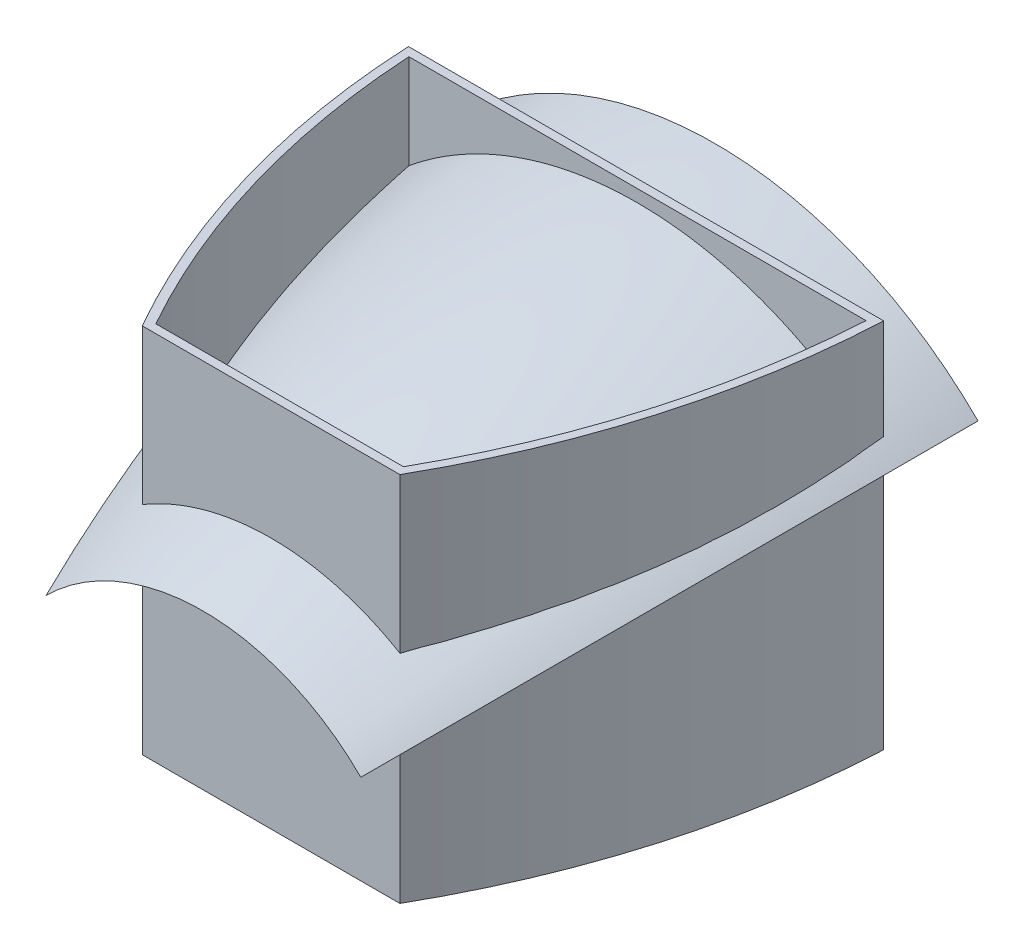
SolidWorks part; units mm, degrees
ref_plane "Спереди" through (0, 0, 0) normal (0, 0, 1) x (1, 0, 0)
ref_plane "Сверху" through (0, 0, 0) normal (0, 1, 0) x (1, 0, 0)
ref_plane "Справа" through (0, 0, 0) normal (1, 0, 0) x (0, 0, -1)
sketch "Эскиз1" plane through (0, 0, 0) normal (0, 1, 0) x (1, 0, 0)
  line L1 (0, 0) -> (0, -131) construction
  line L7 (-45, -131) -> (45, -131)
  line L8 (-83, 0) -> (83, 0)
  arc A0 (-45, -131) -> (-83, 0) centre (208.6832, 13.5989) cw
  arc A2 (45, -131) -> (83, 0) centre (-208.6832, 13.5989) ccw
  point P2 (0, 0)
  point P8 (0, 0)
  point P10 (0, 0)
  point P11 (0, 0)
  point P12 (0, 0)
  point P13 (0, 0)
  point P15 (0, 0)
  point P16 (0, 0)
  point P17 (0, 0)
  point P18 (0, 0)
  point P19 (0, 0)
  point P20 (0, 0)
  point P21 (0, 0)
  point P22 (0, 0)
  dimension "D3" = 292
  dimension "D4" = 131
  dimension "D1" = 166
  dimension "D2" = 90
sketch "Эскиз3" plane through (0, 0, 0) normal (1, 0, 0) x (0, 0, -1)
  line L0 (0, 0) -> (-131, 0) construction
  line L1 (0, 0) -> (-131, 0) construction
  line L2 (0, 0) -> (0, 125) construction
  line L3 (-131, 0) -> (-131, 87) construction
  line L4 (-141, 82.7679) -> (10, 126.6639)
  arc A0 (-141, 82.7679) -> (10, 126.6639) centre (107.5803, -490.6716) cw
  point P8 (-131, 87)
  point P9 (0, 125)
  point P12 (0, 0)
  point P13 (0, 0)
  point P14 (-131, 87)
  point P15 (0, 125)
  dimension "D1" = 125
  dimension "D3" = 10
  dimension "D6" = 625
  dimension "D2" = 87
  dimension "D4" = 131
  dimension "D5" = 10
revolve "Повернуть-Тонкостенный1" add sketch "Эскиз3" angle 90 mid plane about L1
extrude "Бобышка-Вытянуть1" add sketch "Эскиз1" along normal through all separate body contours A2 L8 A0 L7
shell "Оболочка1" thickness 3
sketch "Эскиз4" plane through (0, 129.7508, 0) normal (0, 1, 0) x (1, 0, 0)
  line L0 (79.383, -9.6144) -> (72.7687, -3)
  line L1 (-79.8398, -3) -> (79.8398, -3) construction
  arc A0 (43.2508, -128) -> (79.8398, -3) centre (-208.6832, 13.5989) ccw construction
  dimension "D1" = 5
  dimension "D2" = 45
